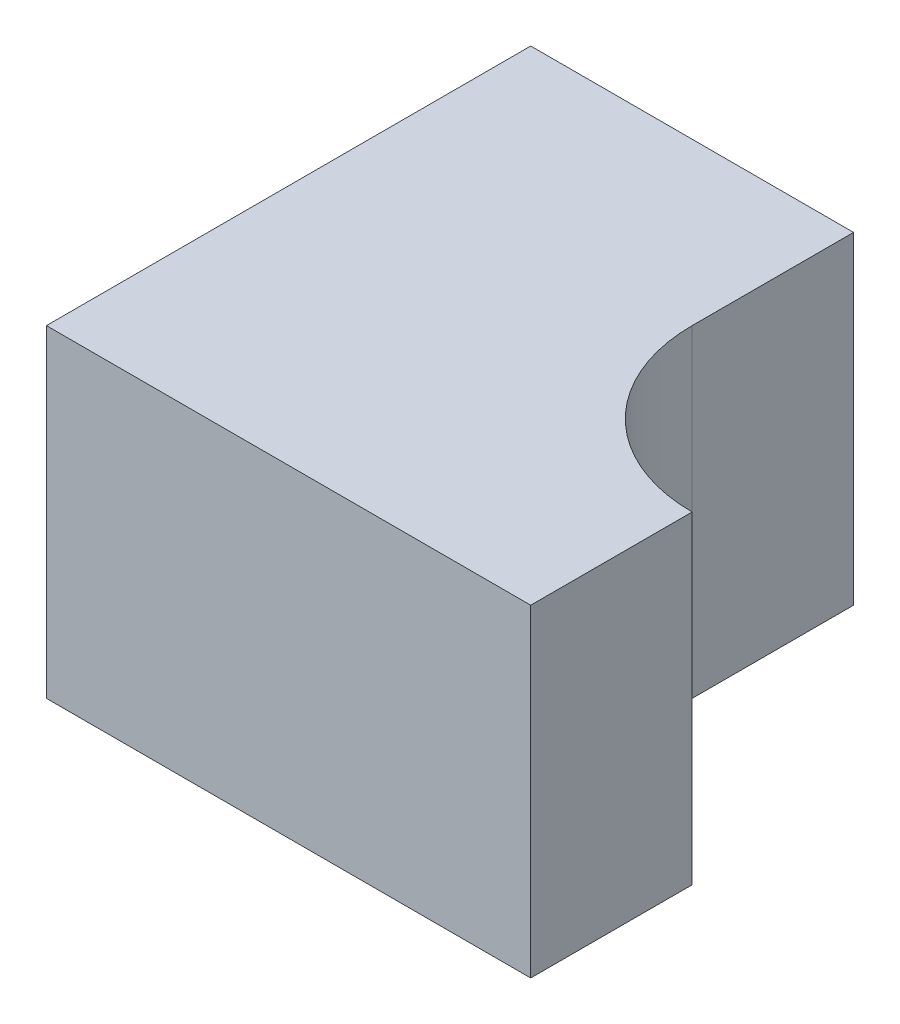
SolidWorks part; units mm, degrees
ref_plane "Přední rovina" through (0, 0, 0) normal (0, 0, 1) x (1, 0, 0)
ref_plane "Horní rovina" through (0, 0, 0) normal (0, 1, 0) x (1, 0, 0)
ref_plane "Pravá rovina" through (0, 0, 0) normal (1, 0, 0) x (0, 0, -1)
sketch "Sketch2" plane through (0, 0, 0) normal (0, 1, 0) x (1, 0, 0)
  line L0 (0, 0) -> (0, -10)
  line L3 (10, -30) -> (-20, -30)
  line L4 (-20, -30) -> (-20, 0)
  line L5 (-20, 0) -> (0, 0)
  line L6 (10, -20) -> (10, -30)
  arc A0 (0, -10) -> (10, -20) centre (10, -10) ccw
  dimension "D2" = 10
  dimension "D1" = 20
  dimension "D4" = 10
extrude "Boss-Extrude1" add sketch "Sketch2" along normal blind 20
equation "\"R\"= 10"
equation "\"D2@Sketch2\"=\"R\""
equation "\"D1@Sketch2\"=\"R\" *2"
equation "\"D4@Sketch2\"=\"R\""
